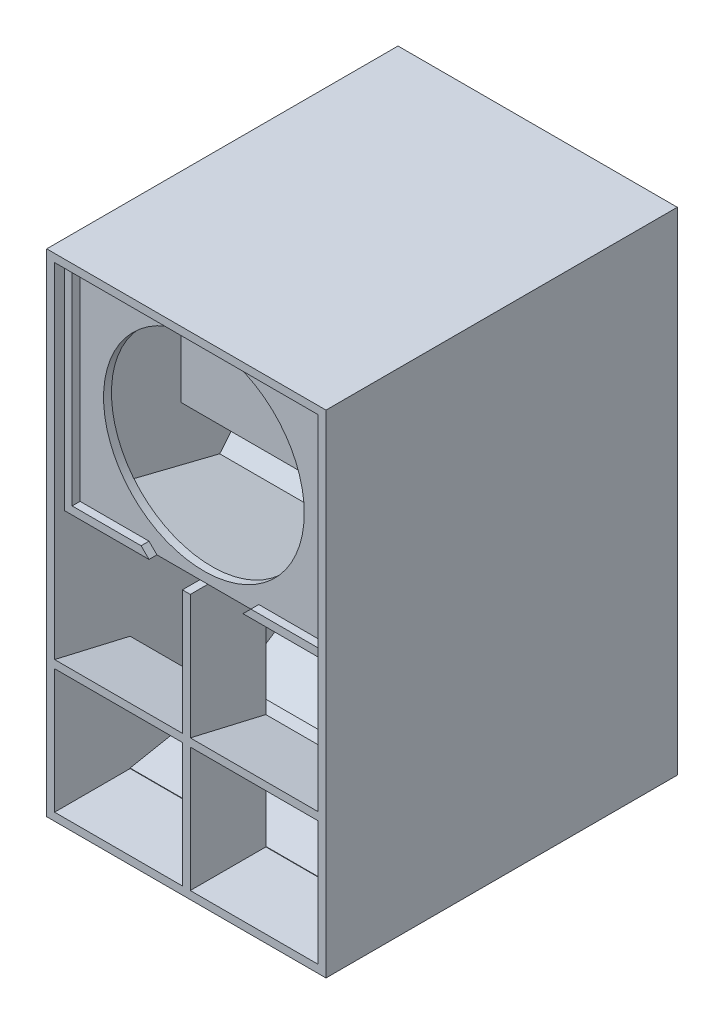
SolidWorks part; units mm, degrees
other "Camera2" [suppressed]
other "Camera3" [suppressed]
ref_plane "Front Plane" through (0, 0, 0) normal (0, 0, 1) x (1, 0, 0)
ref_plane "Top Plane" through (0, 0, 0) normal (0, 1, 0) x (1, 0, 0)
ref_plane "Right Plane" through (0, 0, 0) normal (1, 0, 0) x (0, 0, -1)
sketch "Sketch1" plane through (0, 0, 0) normal (0, 1, 0) x (1, 0, 0)
  line L0 (0, 47.2857) -> (0, -47.1502) construction
  line L2 (-318, -400) -> (318, -400)
  line L3 (-318, -400) -> (-318, 400)
  line L4 (-318, 400) -> (318, 400)
  line L5 (318, -400) -> (318, 400)
  line L6 (-318, -400) -> (318, 400) construction
  line L7 (-318, 400) -> (318, -400) construction
  point P3 (0, 0)
  dimension "D1" = 800
  dimension "D2" = 636
extrude "Boss-Extrude1" add sketch "Sketch1" along normal blind 18
ref_plane "Plane1" through (-318, 0, 0) normal (-1, 0, 0) x (0, 0, 1)
sketch "Sketch3" plane through (-318, 0, 0) normal (-1, 0, 0) x (0, 0, 1)
  line L0 (-400, 18) -> (-400, 0) construction
  line L1 (400, 18) -> (-400, 18)
  line L2 (400, 18) -> (400, 1102)
  line L3 (400, 1102) -> (-400, 1102)
  line L4 (-400, 18) -> (-400, 1102)
  line L5 (112, 1102) -> (112, 682)
  line L6 (94, 1102) -> (94, 682)
  line L7 (112, 682) -> (94, 682)
  line L8 (-21, 1102) -> (94, 967.4489)
  line L9 (2.6787, 1102) -> (94, 995.1532)
  line L10 (173.4588, 967.4489) -> (-512.3103, 967.4489) construction
  line L11 (-382, 1124.6418) -> (-382, -192.1151) construction
  line L12 (0, -341.1044) -> (0, 1466.2906) construction
  line L13 (-382, 967.4489) -> (-226, 1102)
  line L14 (130.607, 995.1532) -> (-639.8305, 995.1532) construction
  line L15 (-382, 991.2192) -> (-253.5596, 1102)
  line L16 (228, 213.0189) -> (228, -333.3534) construction
  line L17 (-393.7563, 981.0793) -> (-237.7563, 1115.6304) construction
  line L18 (-15, 289.1613) -> (-15, 66.3369) construction
  line L19 (-219, 310.9531) -> (-219, -239.3208) construction
  line L20 (-352, -230.7989) -> (-352, 531.6714) construction
  line L21 (157.8001, 48) -> (-1120.4911, 48) construction
  line L22 (-15, 48) -> (139.3366, 18)
  line L23 (-15, 66.3369) -> (228, 19.1025)
  line L24 (-11.5654, 65.6693) -> (142.7712, 35.6693) construction
  line L25 (-15, 48) -> (-15, -289.235) construction
  line L26 (-106.5746, 181) -> (-721.1901, 181) construction
  line L27 (-15, 48) -> (-219, 181)
  line L28 (-15, 66.3369) -> (-219, 199.3369)
  line L30 (-305.1468, 547) -> (-585.2247, 547) construction
  line L31 (-248.011, 382) -> (-455.989, 382) construction
  line L32 (-352, 382) -> (-219, 181)
  line L33 (-339.8666, 382) -> (-219, 199.3369)
  line L34 (-352, 382) -> (-382, 547)
  line L35 (-382, 613.7335) -> (-339.8666, 382)
  line L37 (360, 1236.2322) -> (360, -267.4777) construction
  line L38 (593.4053, 602) -> (206.8269, 602) construction
  line L39 (360, 602) -> (17.4856, 516.6016)
  line L40 (342, 616.0631) -> (24.0446, 536.7879)
  line L41 (355.6454, 619.4653) -> (13.131, 534.0669) construction
  line L42 (-78.8015, 659.3551) -> (24.0446, 536.7879)
  line L43 (17.4856, 516.6016) -> (-96.1276, 652.0005)
  line L45 (0, 530.793) -> (13.131, 534.0669)
  line L46 (-78.8015, 659.3551) -> (-101.3796, 874.1718)
  line L47 (-96.1276, 652.0005) -> (-119.281, 872.2903)
  line L48 (-96.7029, 657.4735) -> (-119.281, 872.2903) construction
  line L49 (-101.3796, 874.1718) -> (-119.281, 872.2903)
  line L50 (342, 597.5121) -> (342, 602)
  line L51 (342, 616.0631) -> (342, 1102)
  line L53 (-382, 547) -> (-382, 613.7335)
  line L54 (228, 19.1025) -> (228, 18)
  line L55 (228, 18) -> (139.3366, 18)
  line L56 (360, 602) -> (360, 1102)
  line L57 (-382, 991.2192) -> (-382, 967.4489)
  point P11 (-21, 1102)
  point P16 (94, 995.1532)
  point P31 (-382, 1102)
  dimension "D1" = 1084
  dimension "D2" = 288
  dimension "D3" = 420
  dimension "D5" = 115
  dimension "D6" = 177
  dimension "D7" = 134.5511
  dimension "D8" = 18
  dimension "D9" = 18
  dimension "D10" = 205
  dimension "D11" = 18
  dimension "D12" = 128.4404
  dimension "D13" = 130.778
  dimension "D14" = 610
  dimension "D15" = 243
  dimension "D16" = 204
  dimension "D17" = 133
  dimension "D18" = 30
  dimension "D19" = 169
  dimension "D21" = 133
  dimension "D22" = 201
  dimension "D23" = 157.897
  dimension "D24" = 165
  dimension "D25" = 156.813
  dimension "D26" = 169.695
  dimension "D27" = 40
  dimension "D28" = 500
  dimension "D29" = 104
  dimension "D31" = 353
  dimension "D32" = 116
  dimension "D33" = 18
  dimension "D34" = 160
  dimension "D35" = 146
  dimension "D36" = 216
  dimension "D38" = 58
  dimension "D4" = 18
  dimension "D20" = 18
  dimension "D30" = 18
  dimension "D37" = 18
extrude "Boss-Extrude2" add sketch "Sketch3" against normal blind 636
sketch "Sketch4" plane through (0, 18, 0) normal (0, 1, 0) x (1, 0, 0)
  line L0 (-318, 1191.8452) -> (-318, -1191.8452) construction
  line L1 (318, 400) -> (-318, 400)
  line L2 (318, 400) -> (318, 382)
  line L3 (318, 382) -> (-318, 382)
  line L4 (-318, 400) -> (-318, 382)
  line L5 (318, 382) -> (-318, 382) construction
  line L6 (-318, 400) -> (-318, -139.3366) construction
extrude "Boss-Extrude3" add sketch "Sketch4" along normal up to vertex (1084 mm away)
sketch "Sketch5" plane through (0, 1102, 0) normal (0, 1, 0) x (1, 0, 0)
  line L0 (-318, 1191.8452) -> (-318, -1191.8452) construction
  line L1 (318, 400) -> (-318, 400)
  line L2 (318, 400) -> (318, -400)
  line L3 (318, -400) -> (-318, -400)
  line L4 (-318, 400) -> (-318, -400)
  line L5 (-318, -400) -> (318, -400) construction
extrude "Boss-Extrude4" add sketch "Sketch5" along normal blind 18
sketch "Sketch6" plane through (0, 18, 0) normal (0, 1, 0) x (1, 0, 0)
  line L0 (0, 473.3104) -> (0, -708.3456) construction
  line L1 (-337.2222, -228) -> (510.0853, -228) construction
  line L2 (-9, -228) -> (9, -228)
  line L3 (-318, -400) -> (318, -400) construction
  line L4 (-9, -228) -> (-9, -400)
  line L5 (9, -228) -> (9, -400)
  line L6 (-432.8051, -400) -> (375.8821, -400) construction
  line L7 (-9, -400) -> (9, -400)
  point P7 (0, -228)
  dimension "D1" = 18
  dimension "D2" = 172
ref_plane "Plane2" through (0, 499.7277, -124.5961) normal (0, 0.9703, -0.2419) x (1, 0, 0)
sketch "Sketch7" plane through (0, 499.7277, -124.5961) normal (0, 0.9703, -0.2419) x (1, 0, 0)
  line L1 (-638.5412, 393.9747) -> (738.7539, 393.9747)
  line L2 (-638.5412, 393.9747) -> (-638.5412, -830.7643)
  line L3 (-638.5412, -830.7643) -> (738.7539, -830.7643)
  line L4 (738.7539, 393.9747) -> (738.7539, -830.7643)
ref_plane "Plane4" through (-9, 0, 0) normal (-1, 0, 0) x (0, 0, 1)
sketch "Sketch10" plane through (-9, 0, 0) normal (-1, 0, 0) x (0, 0, 1)
  line L0 (400, 18) -> (228, 18)
  line L1 (228, 18) -> (228, 569.0887)
  line L2 (400, 18) -> (400, 602)
  line L3 (400, 602) -> (360, 602)
  line L4 (360, 602) -> (228, 569.0887)
  dimension "D1" = 172
  dimension "D2" = 584
  dimension "D3" = 132
extrude "Boss-Extrude6" add sketch "Sketch10" against normal blind 18
sketch "Sketch11" plane through (0, 18, 0) normal (0, 1, 0) x (1, 0, 0)
  line L0 (318, 400) -> (-318, 400) construction
  line L1 (318, -400) -> (300, -400)
  line L2 (318, -400) -> (318, 400)
  line L3 (318, 400) -> (300, 400)
  line L4 (300, -400) -> (300, 400)
  dimension "D1" = 18
extrude "Boss-Extrude7" add sketch "Sketch11" along direction (0, -1, 0) on the side of the normal up to vertex (1084 mm away)
sketch "Sketch12" plane through (0, 0, 400) normal (0, 0, 1) x (1, 0, 0)
  line L0 (318, 1120) -> (318, 0) construction
  line L1 (318, 319) -> (-318, 319)
  line L2 (318, 319) -> (318, 301)
  line L3 (318, 301) -> (-318, 301)
  line L4 (-318, 319) -> (-318, 301)
  line L5 (-318, 1191.8452) -> (-318, -1191.8452) construction
  line L6 (-432.8051, 18) -> (375.8821, 18) construction
  dimension "D1" = 18
  dimension "D2" = 283
sketch "Sketch13" plane through (0, 0, 228) normal (0, 0, -1) x (-1, 0, 0)
  line L0 (-318, 1120) -> (-318, 0) construction
  line L1 (318, 1120) -> (318, 0) construction
  line L2 (-318, 279) -> (318, 279)
  line L3 (-318, 279) -> (-318, 261)
  line L4 (-318, 261) -> (318, 261)
  line L5 (318, 279) -> (318, 261)
  line L6 (432.8051, 18) -> (-375.8821, 18) construction
  dimension "D1" = 18
  dimension "D2" = 243
sketch "Sketch14" plane through (-9, 0, 0) normal (-1, 0, 0) x (0, 0, 1)
  line L0 (228, 569.0887) -> (228, 19.1025) construction
  line L3 (228, 18) -> (400, 18) construction
  line L4 (400, 319) -> (400, 301) construction
  line L5 (400, 18) -> (400, 602) construction
  line L6 (228, 261) -> (400, 301)
  point P0 (228, 261)
  point P5 (400, 301)
  dimension "D1" = 243
  dimension "D2" = 283
sweep "Sweep1" add profiles "Sketch13" path "Sketch14"
sketch "Sketch15" plane through (0, 18, 0) normal (0, 1, 0) x (1, 0, 0)
  line L0 (318, 400) -> (-318, 400) construction
  line L1 (-318, -400) -> (-300, -400)
  line L2 (-318, -400) -> (-318, 400)
  line L3 (-318, 400) -> (-300, 400)
  line L4 (-300, -400) -> (-300, 400)
  line L5 (318, 400) -> (-318, 400) construction
  dimension "D1" = 18
extrude "Boss-Extrude8" add sketch "Sketch15" along direction (0, -1, 0) on the side of the normal up to vertex (1084 mm away)
sketch "Sketch16" plane through (0, 0, 360) normal (0, 0, 1) x (1, 0, 0)
  line L0 (0, -19.9671) -> (0, 1432.9092) construction
  line L1 (300, 602) -> (9, 602) construction
  line L2 (300, 1102) -> (-300, 1102) construction
  line L3 (-525.2256, 852) -> (626.652, 852) construction
  line L4 (-300, 1102) -> (300, 1102) construction
  circle A0 centre (0, 852) radius 228.5
  dimension "D3" = 457
  dimension "D1" = 500
  dimension "D2" = 250
extrude "Cut-Extrude1" cut sketch "Sketch16" against normal blind 18.1
sketch "Sketch17" plane through (0, 0, 360) normal (0, 0, 1) x (1, 0, 0)
  line L0 (-107, 1166.2631) -> (-107, 1059.4372) construction
  line L1 (-300, 1102) -> (-300, 319) construction
  line L2 (-282, 1084) -> (-125, 1084)
  line L3 (-300, 1102) -> (300, 1102) construction
  line L4 (-300, 1102) -> (-107, 1102)
  line L5 (300, 1102) -> (-300, 1102) construction
  line L6 (-300, 1069.4654) -> (-300, 1142.7041) construction
  line L7 (-300, 1102) -> (-300, 602) construction
  line L8 (-125, 1084) -> (-107, 1102)
  line L9 (-282, 1433.2093) -> (-282, 531.8035) construction
  line L10 (-282, 1084) -> (-282, 620)
  line L12 (-572.7361, 852) -> (475.0981, 852) construction
  line L13 (0, -13.0523) -> (0, 1524.0105) construction
  line L14 (-300, 1102) -> (-300, 1084)
  line L15 (-125, 620) -> (-107, 602)
  line L16 (-282, 620) -> (-125, 620)
  line L17 (-300, 602) -> (-107, 602)
  line L18 (300, 1102) -> (300, 602)
  line L19 (125, 1084) -> (107, 1102)
  line L20 (282, 1084) -> (125, 1084)
  line L21 (300, 1102) -> (107, 1102)
  line L22 (282, 602) -> (282, 1084)
  line L24 (300, 602) -> (107, 602)
  line L25 (125, 620) -> (107, 602)
  line L26 (300, 620) -> (125, 620)
  line M16 (300, 1102) -> (-300, 1102)
  line M17 (-300, 1102) -> (-300, 602)
  line M18 (-300, 602) -> (-9, 602)
  line M20 (9, 602) -> (300, 602)
  line M21 (300, 602) -> (300, 1102)
  dimension "D1" = 193
  dimension "D2" = 18
  dimension "D3" = 175
  dimension "D4" = 18
  dimension "D5" = 250
  dimension "D6" = 18
extrude "Boss-Extrude9" add sketch "Sketch17" along normal blind 18 contours L26 L18 L19 L20 L22 M16 | L16 L10 L2 L8 L15 M16 M17 M18 | L26 L22 M21 M20 | L22 L26 L25 M20
